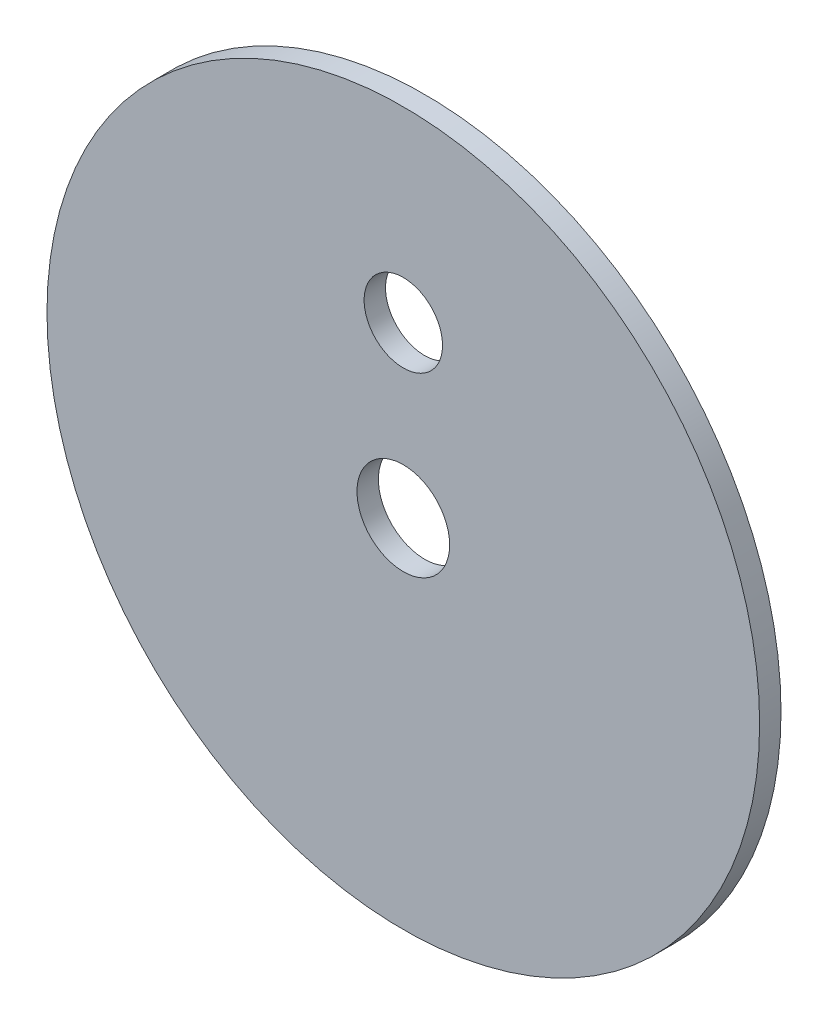
SolidWorks part; units mm, degrees
ref_plane "Ebene vorne" through (0, 0, 0) normal (0, 0, 1) x (1, 0, 0)
ref_plane "Ebene oben" through (0, 0, 0) normal (0, 1, 0) x (1, 0, 0)
ref_plane "Ebene rechts" through (0, 0, 0) normal (1, 0, 0) x (0, 0, -1)
sketch "Skizze1" plane through (0, 0, 0) normal (0, 0, 1) x (1, 0, 0)
  circle A0 centre (0, 0) radius 50
extrude "Aufsatz-Linear austragen1" add sketch "Skizze1" along normal blind 3
sketch "Skizze2" plane through (0, 0, 3) normal (0, 0, 1) x (1, 0, 0)
  circle A0 centre (0, 0) radius 6.5
  circle A1 centre (0, 23.75) radius 5.5
  dimension "D1" = 11
  dimension "D2" = 13
  dimension "D3" = 23.75
extrude "Schnitt-Linear austragen1" cut sketch "Skizze2" against normal through all both and the other way through all
